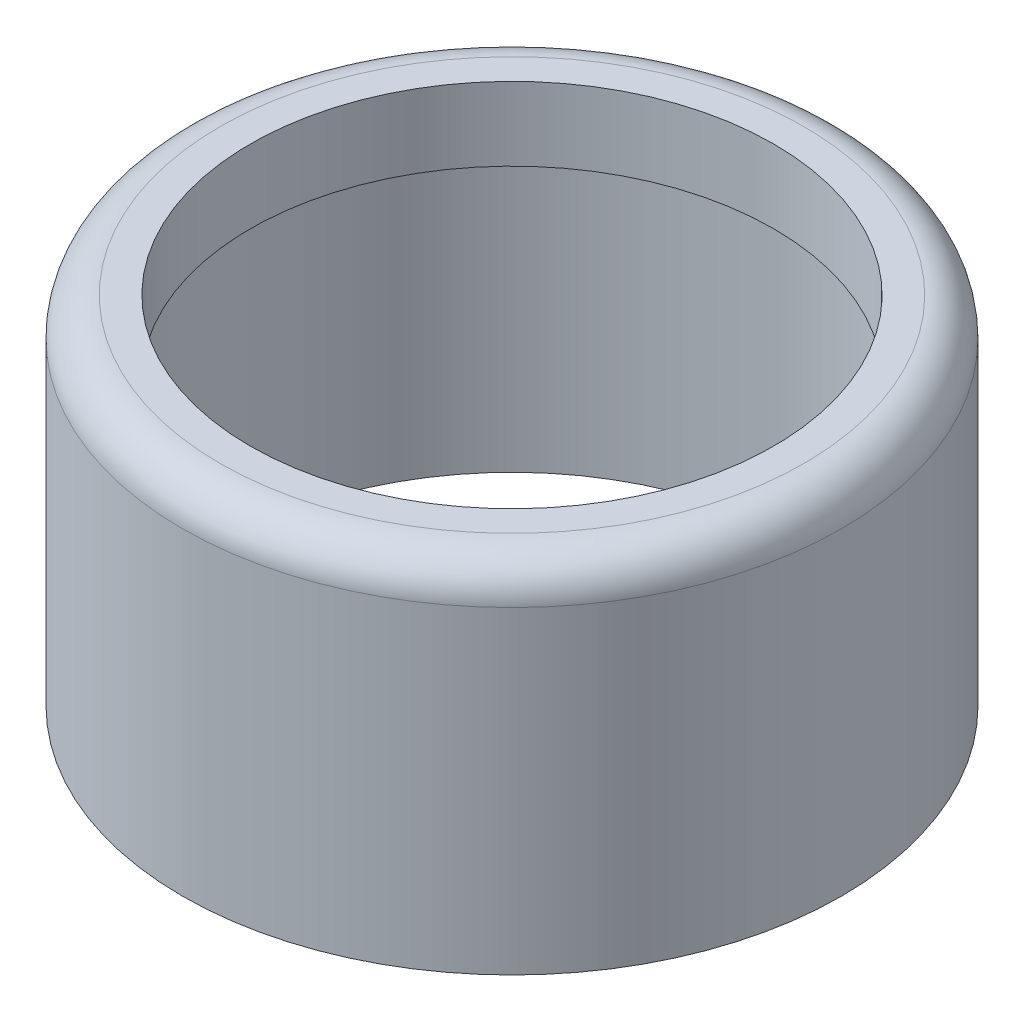
SolidWorks part; units mm, degrees
ref_plane "Front Plane" through (0, 0, 0) normal (0, 0, 1) x (1, 0, 0)
ref_plane "Top Plane" through (0, 0, 0) normal (0, 1, 0) x (1, 0, 0)
ref_plane "Right Plane" through (0, 0, 0) normal (1, 0, 0) x (0, 0, -1)
sketch "Sketch1" plane through (0, 0, 0) normal (0, 0, 1) x (1, 0, 0)
  line L0 (0, 0) -> (0, -42.3795) construction
  line L1 (15.2, -19.8624) -> (15.2, -4.8624)
  line L2 (15.2, -4.8624) -> (13.9, -4.8624)
  line L3 (13.9, -4.8624) -> (13.9, -0.9624)
  line L4 (13.9, -0.9624) -> (15.5, -0.9624)
  line L5 (17.5, -2.9624) -> (17.5, -19.8624)
  line L6 (17.5, -19.8624) -> (15.2, -19.8624)
  arc A0 (17.5, -2.9624) -> (15.5, -0.9624) centre (15.5, -2.9624) ccw
  point P11 (17.5, -0.9624)
  dimension "D6" = 2
  dimension "D1" = 15.2
  dimension "D2" = 3.6
  dimension "D3" = 15
  dimension "D4" = 18.9
  dimension "D5" = 2.3
revolve "Revolve1" add sketch "Sketch1" angle 360 about L0
